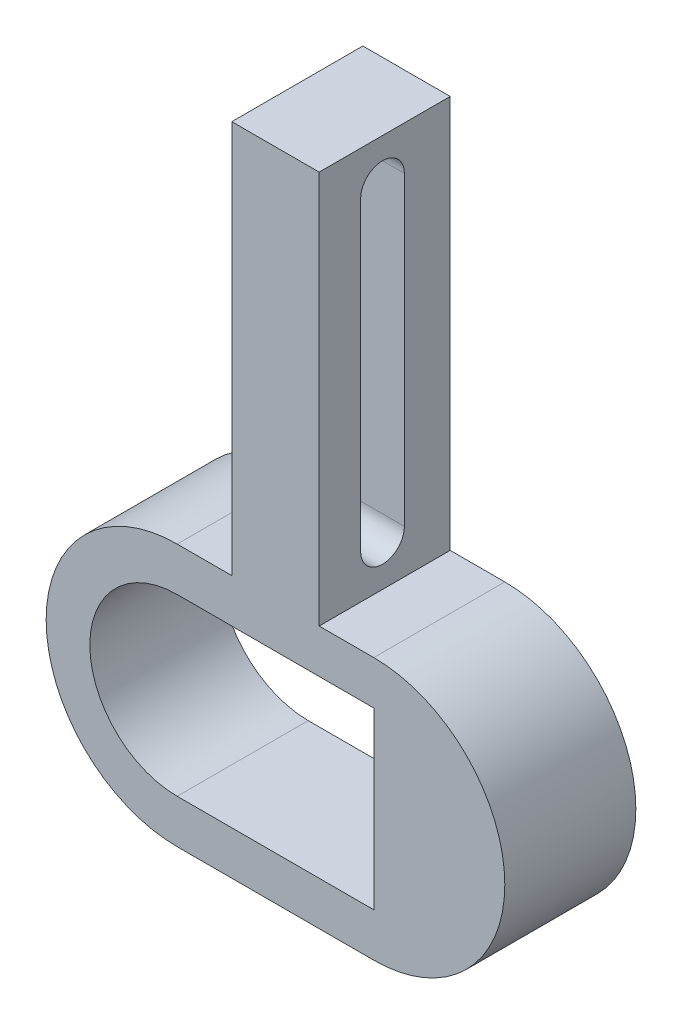
SolidWorks part; units mm, degrees
ref_plane "Alzado" through (0, 0, 0) normal (0, 0, 1) x (1, 0, 0)
ref_plane "Planta" through (0, 0, 0) normal (0, 1, 0) x (1, 0, 0)
ref_plane "Vista lateral" through (0, 0, 0) normal (1, 0, 0) x (0, 0, -1)
sketch "Croquis1" plane through (0, 0, 0) normal (0, 0, 1) x (1, 0, 0)
  line L0 (0, 0) -> (20, 0)
  line L1 (20, 0) -> (20, -90)
  line L4 (-12.5, -90) -> (0, -90)
  line L10 (0, -90) -> (0, 0)
  line L11 (32.5, -140) -> (-12.5, -140)
  line L12 (32.5, -140) -> (32.5, -100)
  line L13 (32.5, -100) -> (-12.5, -100)
  line L15 (32.5, -140) -> (-12.5, -100) construction
  line L16 (32.5, -100) -> (-12.5, -140) construction
  line L17 (-12.5, -150) -> (32.5, -150)
  line L19 (20, -90) -> (32.5, -90)
  arc A4 (-12.5, -100) -> (-12.5, -140) centre (-12.5, -120) ccw
  arc A5 (-12.5, -90) -> (-12.5, -150) centre (-12.5, -120) ccw
  arc A6 (32.5, -150) -> (32.5, -90) centre (32.5, -120) ccw
  point P3 (10, -120)
  point P7 (10, -120)
  point P13 (10, -130.3567)
  dimension "D8" = 30
  dimension "D9" = 30
  dimension "D7" = 20
  dimension "D1" = 20
  dimension "D2" = 90
  dimension "D3" = 12.5
  dimension "D4" = 45
  dimension "D5" = 40
  dimension "D6" = 10
extrude "Saliente-Extruir1" add sketch "Croquis1" along normal blind 30
sketch "Croquis3" plane through (20, 0, 0) normal (1, 0, 0) x (0, 0, -1)
  line L0 (-15.4978, -10) -> (-15.4978, -80) construction
  line L1 (-10.4978, -10) -> (-10.4978, -80)
  line L2 (-20.4978, -10) -> (-20.4978, -80)
  line L3 (-30, 0) -> (0, 0) construction
  arc A0 (-10.4978, -10) -> (-20.4978, -10) centre (-15.4978, -10) ccw
  arc A1 (-20.4978, -80) -> (-10.4978, -80) centre (-15.4978, -80) ccw
  point P2 (-15.4978, -45)
  dimension "D1" = 5
  dimension "D3" = 10
  dimension "D2" = 70
  dimension "D4" = 10
  dimension "D5" = 15.4978
extrude "Cortar-Extruir1" cut sketch "Croquis3" against normal blind 30
